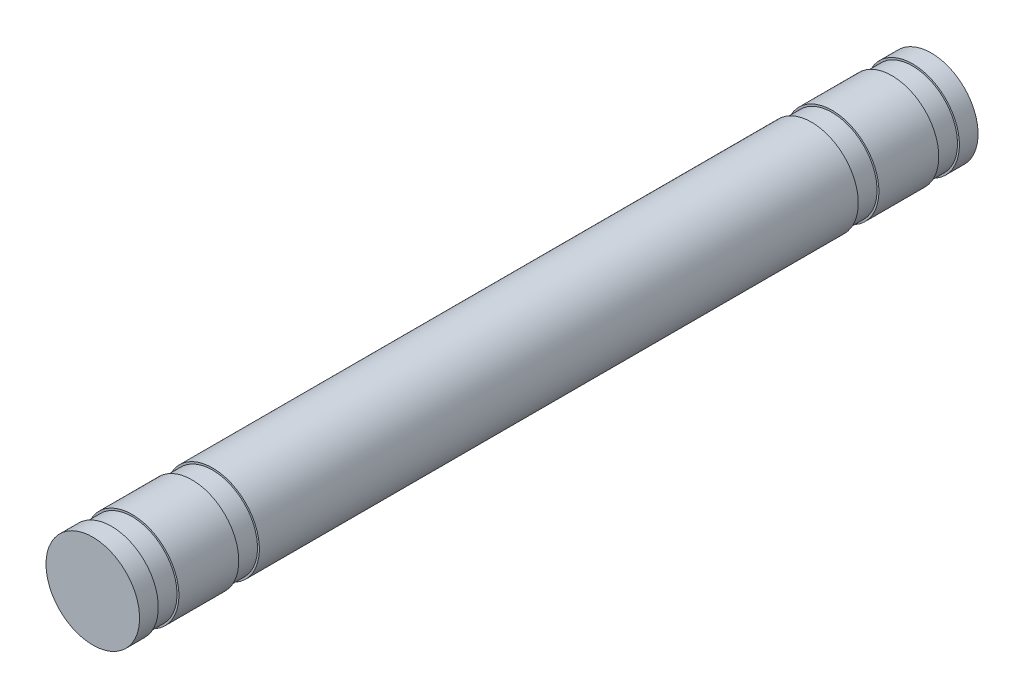
SolidWorks part; units mm, degrees
material "Plain Carbon Steel"
ref_plane "Front Plane" through (0, 0, 0) normal (0, 0, 1) x (1, 0, 0)
ref_plane "Top Plane" through (0, 0, 0) normal (0, 1, 0) x (1, 0, 0)
ref_plane "Right Plane" through (0, 0, 0) normal (1, 0, 0) x (0, 0, -1)
sketch "Sketch1" plane through (0, 0, 0) normal (0, 1, 0) x (1, 0, 0)
  line L0 (0, 0) -> (-2.5, 0)
  line L1 (-2.5, 0) -> (-2.5, 1)
  line L13 (-2.5, 43.8) -> (-2.5, 44.8)
  line L14 (-2.5, 44.8) -> (0, 44.8)
  line L15 (0, 44.8) -> (0, 0)
  line L16 (-2.5, 1) -> (-2.4, 1)
  line L17 (-2.4, 1) -> (-2.4, 2.1)
  line L18 (-2.4, 2.1) -> (-2.5, 2.1)
  line L19 (-2.5, 2.1) -> (-2.5, 5.3)
  line L20 (-2.5, 5.3) -> (-2.4, 5.3)
  line L21 (-2.4, 5.3) -> (-2.4, 6.4)
  line L22 (-2.4, 6.4) -> (-2.5, 6.4)
  line L23 (-2.5, 6.4) -> (-2.5, 38.4)
  line L24 (-2.5, 38.4) -> (-2.4, 38.4)
  line L25 (-2.4, 38.4) -> (-2.4, 39.5)
  line L26 (-2.4, 39.5) -> (-2.5, 39.5)
  line L27 (-2.5, 39.5) -> (-2.5, 42.7)
  line L28 (-2.5, 42.7) -> (-2.4, 42.7)
  line L32 (-2.4, 42.7) -> (-2.4, 43.8)
  line L33 (-2.4, 43.8) -> (-2.5, 43.8)
  line L34 (-2.5, 22.4) -> (0, 22.4) construction
  dimension "D1" = 2.5
  dimension "D2" = 1
  dimension "D3" = 2.4
  dimension "D4" = 1.1
  dimension "D5" = 3.2
  dimension "D6" = 44.8
revolve "Revolve1" add sketch "Sketch1" angle 360 about L15
equation "\"weightkg\"= \"SW-Mass\" / 1000"
